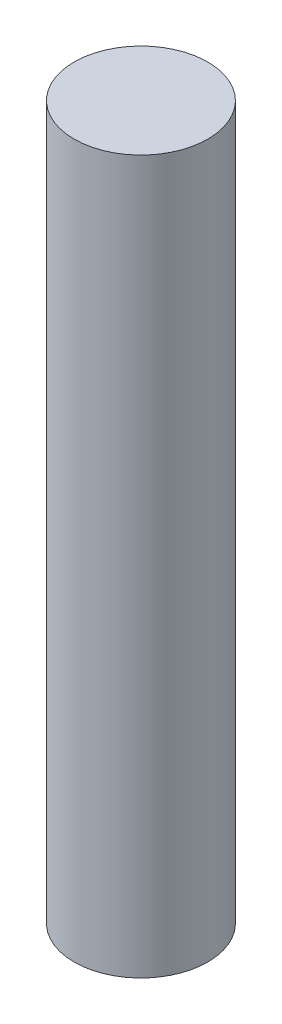
SolidWorks part; units mm, degrees
ref_plane "Front Plane" through (0, 0, 0) normal (0, 0, 1) x (1, 0, 0)
ref_plane "Top Plane" through (0, 0, 0) normal (0, 1, 0) x (1, 0, 0)
ref_plane "Right Plane" through (0, 0, 0) normal (1, 0, 0) x (0, 0, -1)
sketch "Sketch1" plane through (0, 0, 0) normal (0, 1, 0) x (1, 0, 0)
  circle A0 centre (0, 0) radius 9.525
  dimension "D1" = 19.05
extrude "Boss-Extrude1" add sketch "Sketch1" against normal blind 101.6
